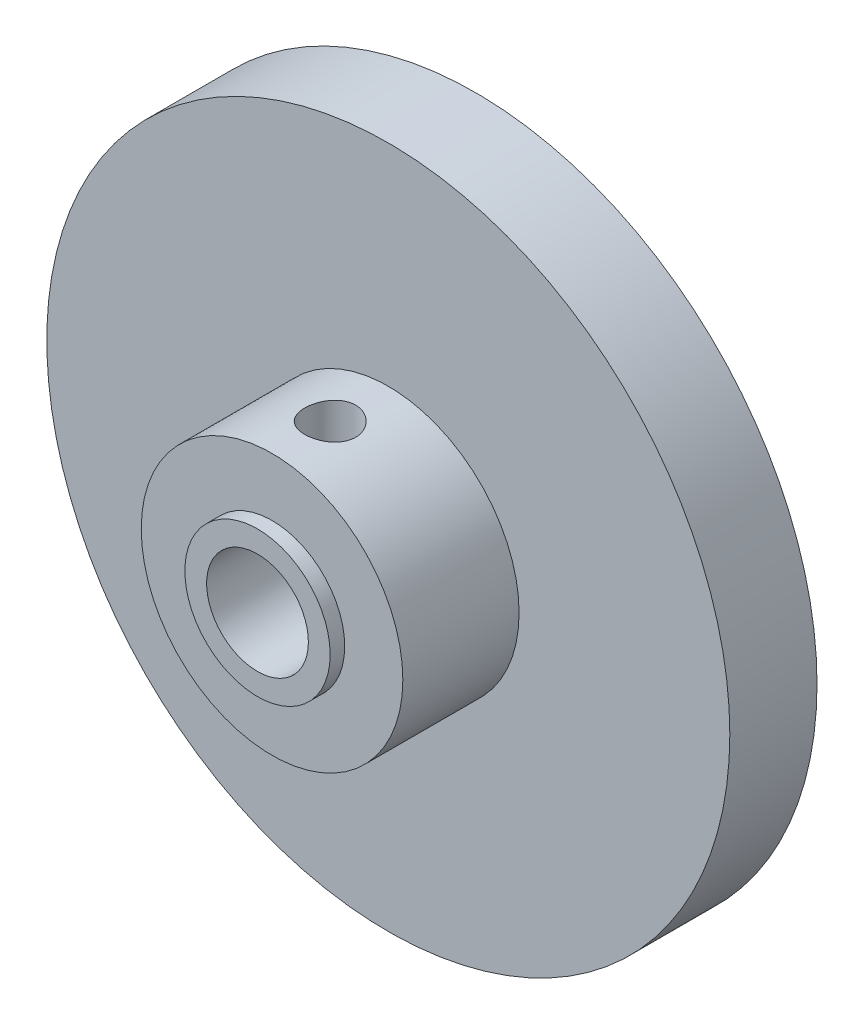
SolidWorks part; units mm, degrees
ref_plane "前视基准面" through (0, 0, 0) normal (0, 0, 1) x (1, 0, 0)
ref_plane "上视基准面" through (0, 0, 0) normal (0, 1, 0) x (1, 0, 0)
ref_plane "右视基准面" through (0, 0, 0) normal (1, 0, 0) x (0, 0, -1)
sketch "草图1" plane through (0, 0, 0) normal (0, 0, 1) x (1, 0, 0)
  circle A0 centre (0, 0) radius 23.5
  dimension "D1" = 47
extrude "凸台-拉伸1" add sketch "草图1" along normal blind 6
sketch "草图2" plane through (0, 0, 6) normal (0, 0, 1) x (1, 0, 0)
  circle A0 centre (0, 0) radius 9
  dimension "D1" = 18
extrude "凸台-拉伸2" add sketch "草图2" along normal blind 8
sketch "草图3" plane through (0, 0, 14) normal (0, 0, 1) x (1, 0, 0)
  circle A0 centre (0, 0) radius 3.5
  dimension "D1" = 7
extrude "切除-拉伸1" cut sketch "草图3" against normal through all
sketch "草图4" plane through (0, 0, 0) normal (0, 1, 0) x (1, 0, 0)
  line L0 (0, -6) -> (0, -14) construction
  line L1 (-9, -6) -> (9, -6) construction
  line L2 (-9, -14) -> (9, -14) construction
  circle A0 centre (0, -10) radius 1.75
  dimension "D1" = 3.5
extrude "切除-拉伸2" cut sketch "草图4" along normal through all
sketch "草图5" plane through (0, 0, 14) normal (0, 0, 1) x (1, 0, 0)
  circle A0 centre (0, 0) radius 3.5
  circle A1 centre (0, 0) radius 5
  dimension "D1" = 1.5
extrude "凸台-拉伸3" add sketch "草图5" along normal blind 1
